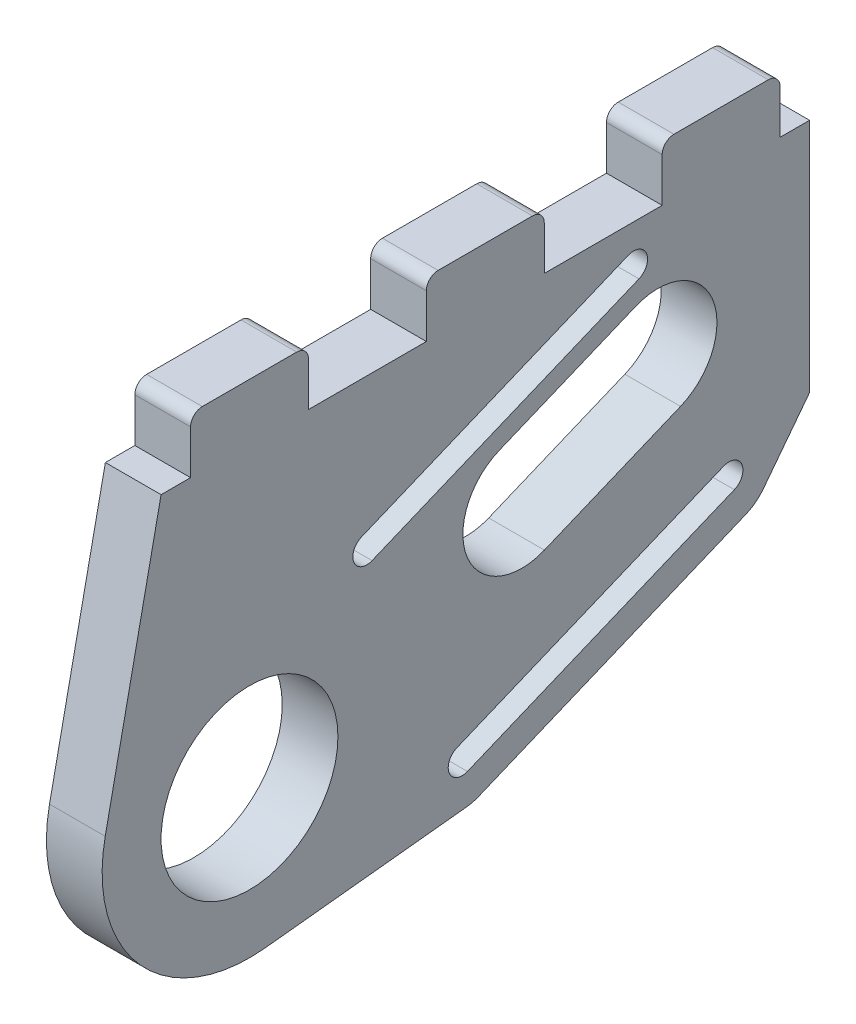
SolidWorks part; units mm, degrees
ref_plane "Front Plane" through (0, 0, 0) normal (0, 0, 1) x (1, 0, 0)
ref_plane "Top Plane" through (0, 0, 0) normal (0, 1, 0) x (1, 0, 0)
ref_plane "Right Plane" through (0, 0, 0) normal (1, 0, 0) x (0, 0, -1)
sketch "Sketch1" plane through (0, 0, 0) normal (1, 0, 0) x (0, 0, -1)
  line L0 (-41.4563, 38.1) -> (38.3452, 38.1) construction
  line L1 (-15.541, 3.2395) -> (-9.525, 32.1)
  line L2 (38.9021, 32.1) -> (-38.9021, 32.1) construction
  line L3 (38.9021, 32.1) -> (38.9021, 38.1) construction
  line L4 (38.9021, 38.1) -> (-38.9021, 38.1) construction
  line L5 (-38.9021, 32.1) -> (-38.9021, 38.1) construction
  line L6 (38.9021, 32.1) -> (-38.9021, 38.1) construction
  line L7 (38.9021, 38.1) -> (-38.9021, 32.1) construction
  line L8 (0, 7.3323) -> (-6.35, 3.6662) construction
  line L9 (-6.35, 3.6662) -> (-6.35, -3.6662) construction
  line L10 (-6.35, -3.6662) -> (0, -7.3323) construction
  line L11 (0, -7.3323) -> (6.35, -3.6662) construction
  line L12 (6.35, -3.6662) -> (6.35, 3.6662) construction
  line L13 (6.35, 3.6662) -> (0, 7.3323) construction
  line L14 (-9.525, 32.1) -> (60.325, 32.1)
  line L15 (0, -15.875) -> (60.325, -15.875)
  line L16 (60.325, -15.875) -> (60.325, 32.1)
  circle A0 centre (0, 0) radius 9.525
  arc A1 (-15.541, 3.2395) -> (0, -15.875) centre (0, 0) ccw
  circle A2 centre (0, 0) radius 25.4 construction
  circle A3 centre (0, 0) radius 6.35 construction
  arc A4 (0, -15.875) -> (-15.541, 3.2395) centre (0, 0) ccw construction
  point P7 (0, 35.1)
  dimension "D1" = 19.05
  dimension "D2" = 6.35
  dimension "D4" = 50.8
  dimension "D3" = 38.1
  dimension "D5" = 6
  dimension "D6" = 12.7
  dimension "D7" = 9.525
  dimension "D8" = 60.325
extrude "Boss-Extrude1" add sketch "Sketch1" along normal mid plane 6
sketch "Sketch2" plane through (3, 0, 0) normal (1, 0, 0) x (0, 0, -1)
  line L0 (0, 0) -> (35.1998, 14.5802) construction
  line L1 (1.6762, -15.7863) -> (23.3965, -13.4799)
  line L2 (29.3332, 12.1502) -> (43.9998, 18.2253) construction
  line L3 (26.9031, 18.0168) -> (41.5697, 24.0919)
  line L4 (31.7632, 6.2836) -> (46.4298, 12.3587)
  line L5 (22.9029, -8.8311) -> (51.6494, 3.0761) construction
  line L6 (22.3289, -7.4452) -> (51.0754, 4.4619)
  line L7 (23.4769, -10.2169) -> (52.2234, 1.6903)
  line L8 (12.6291, 15.9721) -> (41.3756, 27.8793) construction
  line L9 (12.055, 17.358) -> (40.8015, 29.2651)
  line L10 (13.2031, 14.5863) -> (41.9496, 26.4935)
  line L11 (12.6291, 15.9721) -> (22.9029, -8.8311) construction
  line L12 (41.3756, 27.8793) -> (51.6494, 3.0761) construction
  line L13 (28.6437, 8.0763) -> (36.8154, 18.7257) construction
  line L14 (42.9639, 14.0078) -> (30.6669, 23.4436) construction
  line L15 (30.6669, 23.4436) -> (16.3468, 17.5121) construction
  line L16 (16.3468, 17.5121) -> (14.3236, 2.1447) construction
  line L17 (14.3236, 2.1447) -> (26.6206, -7.2911) construction
  line L18 (26.6206, -7.2911) -> (40.9407, -1.3595) construction
  line L19 (40.9407, -1.3595) -> (42.9639, 14.0078) construction
  line L20 (21.1138, -4.5119) -> (49.8603, 7.3953) construction
  line L21 (24.6919, -13.1502) -> (53.4384, -1.243) construction
  line L22 (0, 0) -> (15.49, 0) construction
  line L23 (0, -15.875) -> (60.325, -15.875)
  line L24 (60.325, -15.875) -> (60.325, 6.7)
  line L25 (60.325, -15.875) -> (60.325, 32.1) construction
  line L26 (60.325, 6.7) -> (55.3577, 0.2294)
  line L27 (53.4384, -1.243) -> (24.6919, -13.1502)
  arc A0 (26.9031, 18.0168) -> (31.7632, 6.2836) centre (29.3332, 12.1502) ccw
  arc A1 (46.4298, 12.3587) -> (41.5697, 24.0919) centre (43.9998, 18.2253) ccw
  arc A2 (22.3289, -7.4452) -> (23.4769, -10.2169) centre (22.9029, -8.8311) ccw
  arc A3 (52.2234, 1.6903) -> (51.0754, 4.4619) centre (51.6494, 3.0761) ccw
  arc A4 (12.055, 17.358) -> (13.2031, 14.5863) centre (12.6291, 15.9721) ccw
  arc A5 (41.9496, 26.4935) -> (40.8015, 29.2651) centre (41.3756, 27.8793) ccw
  circle A6 centre (32.9051, 13.6297) radius 6.477 construction
  circle A7 centre (28.6437, 8.0763) radius 13.4234 construction
  arc A8 (53.4384, -1.243) -> (49.8603, 7.3953) centre (51.6494, 3.0761) ccw construction
  arc A9 (21.1138, -4.5119) -> (24.6919, -13.1502) centre (22.9029, -8.8311) ccw construction
  circle A10 centre (0, 0) radius 15.875 construction
  arc A13 (-15.541, 3.2395) -> (0, -15.875) centre (0, 0) ccw construction
  arc A14 (1.6762, -15.7863) -> (0, -15.875) centre (0, 0) cw
  arc A15 (55.3577, 0.2294) -> (53.4384, -1.243) centre (51.6494, 3.0761) cw
  arc A16 (24.6919, -13.1502) -> (23.3965, -13.4799) centre (22.9029, -8.8311) cw
  point P7 (36.6665, 15.1877)
  point P14 (37.2761, -2.8775)
  point P19 (27.0023, 21.9257)
  dimension "D2" = 12.7
  dimension "D5" = 1.5
  dimension "D8" = 12.954
  dimension "D1" = 38.1
  dimension "D3" = 15.875
  dimension "D4" = 31.75
  dimension "D6" = 31
  dimension "D7" = 7
  dimension "D9" = 13.97
  dimension "D10" = 1.27
  dimension "D12" = 22.5
  dimension "D13" = 25.4
  dimension "D11" = 3.175
extrude "Cut-Extrude1" cut sketch "Sketch2" against normal through all
sketch "Sketch3" plane through (0, 32.1, 0) normal (0, 1, 0) x (1, 0, 0)
  line L0 (3, 60.325) -> (3, -9.525) construction
  line L1 (-3, -6.35) -> (3, -6.35)
  line L2 (-3, -6.35) -> (-3, 6.35)
  line L3 (-3, 6.35) -> (3, 6.35)
  line L4 (3, -6.35) -> (3, 6.35)
  line L5 (-3, -6.35) -> (3, 6.35) construction
  line L6 (-3, 6.35) -> (3, -6.35) construction
  point P0 (0, 0)
  dimension "D1" = 12.7
extrude "Boss-Extrude2" add sketch "Sketch3" along normal blind 6
fillet "Fillet1" radius 1.27 2 edges at (0, 38.1, -6.35) (0, 38.1, 6.35)
pattern_linear "LPattern1" count 3 spacing 25.4 along (0, 0, -1) of "Boss-Extrude2", "Fillet1"
equation "\"D6@Sketch2\"=31mm"
equation "\"D7@Sketch2\"=7mm"
